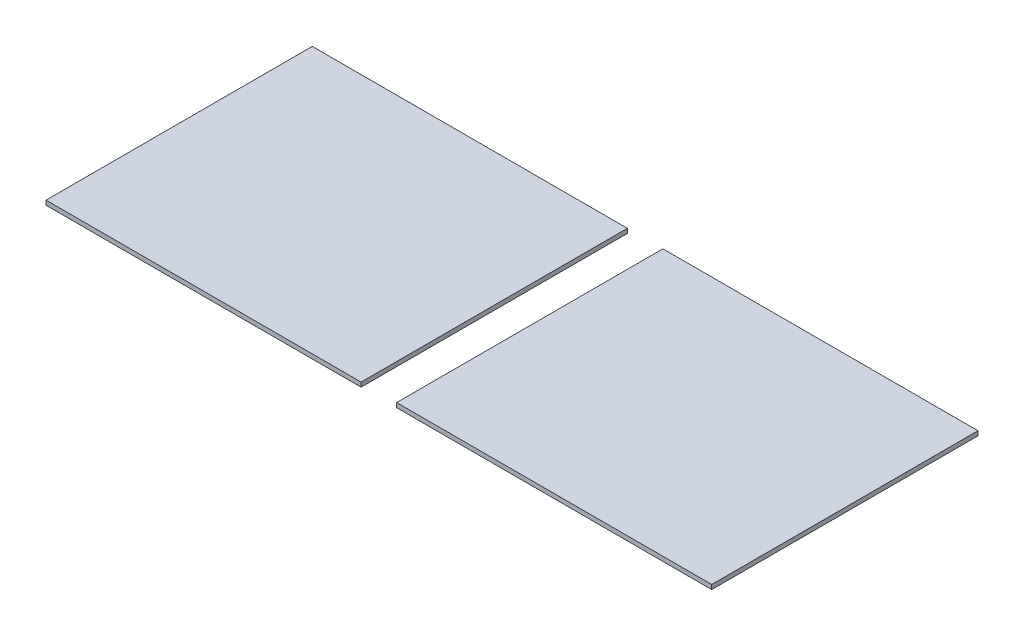
SolidWorks part; units mm, degrees
ref_plane "Front Plane" through (0, 0, 0) normal (0, 0, 1) x (1, 0, 0)
ref_plane "Top Plane" through (0, 0, 0) normal (0, 1, 0) x (1, 0, 0)
ref_plane "Right Plane" through (0, 0, 0) normal (1, 0, 0) x (0, 0, -1)
sketch "Sketch1" plane through (0, 0, 0) normal (0, 1, 0) x (1, 0, 0)
  line L1 (0, 0) -> (1219.2, 0)
  line L2 (0, 0) -> (0, 609.6)
  line L3 (0, 609.6) -> (1219.2, 609.6)
  line L4 (1219.2, 0) -> (1219.2, 609.6)
  dimension "D1" = 1219.2
  dimension "D2" = 609.6
extrude "Boss-Extrude1" add sketch "Sketch1" along normal blind 6.35
sketch "Sketch2" plane through (0, 6.35, 0) normal (0, 1, 0) x (1, 0, 0)
  line L0 (0, 0) -> (1219.2, 0) construction
  line L1 (0, 0) -> (450.85, 0)
  line L2 (0, 0) -> (0, 381)
  line L3 (0, 381) -> (450.85, 381)
  line L4 (450.85, 0) -> (450.85, 381)
  line L5 (501.65, 0) -> (952.5, 0)
  line L6 (501.65, 0) -> (501.65, 381)
  line L7 (501.65, 381) -> (952.5, 381)
  line L8 (952.5, 0) -> (952.5, 381)
  line L9 (0, 609.6) -> (1219.2, 609.6)
  line L10 (1219.2, 609.6) -> (1219.2, 0)
  line L11 (1219.2, 0) -> (952.5, 0)
  line L12 (952.5, 0) -> (952.5, 381)
  line L13 (952.5, 381) -> (501.65, 381)
  line L14 (501.65, 381) -> (501.65, 0)
  line L16 (450.85, 0) -> (450.85, 381)
  line L17 (450.85, 381) -> (0, 381)
  line L18 (0, 609.6) -> (0, 381)
  line L19 (0, 381) -> (450.85, 381)
  line L20 (450.85, 381) -> (450.85, 0)
  line L21 (450.85, 0) -> (501.65, 0)
  line L22 (501.65, 0) -> (501.65, 381)
  line L23 (501.65, 381) -> (952.5, 381)
  line L24 (952.5, 381) -> (952.5, 0)
  line L25 (952.5, 0) -> (1219.2, 0)
  line L26 (1219.2, 0) -> (1219.2, 609.6)
  line L27 (1219.2, 609.6) -> (0, 609.6)
  line L28 (450.85, 381) -> (501.65, 381)
  line L29 (450.85, 381) -> (450.85, 0)
  line L30 (450.85, 0) -> (501.65, 0)
  line L31 (501.65, 381) -> (501.65, 0)
  line L32 (0, 609.6) -> (1219.2, 609.6)
  line L33 (0, 609.6) -> (0, 381)
  line L34 (0, 381) -> (1219.2, 381)
  line L35 (1219.2, 609.6) -> (1219.2, 381)
  line L36 (952.5, 381) -> (1219.2, 381)
  line L37 (952.5, 381) -> (952.5, 0)
  line L38 (952.5, 0) -> (1219.2, 0)
  line L39 (1219.2, 381) -> (1219.2, 0)
  point P18 (0, 0)
  point P19 (0, 0)
  point P20 (0, 0)
  point P21 (501.65, 381)
  point P22 (0, 0)
  dimension "D1" = 450.85
  dimension "D2" = 381
  dimension "D3" = 450.85
  dimension "D5" = 50.8
sketch "Sketch7" plane through (0, 6.35, 0) normal (0, 1, 0) x (1, 0, 0)
  line L0 (501.65, 381) -> (952.5, 381)
  line L1 (0, 609.6) -> (1219.2, 609.6)
  line L2 (0, 609.6) -> (0, 381)
  line L3 (0, 381) -> (450.85, 381)
  line L4 (1219.2, 609.6) -> (1219.2, 381)
  line L6 (952.5, 381) -> (952.5, 0)
  line L7 (952.5, 0) -> (1219.2, 0)
  line L8 (1219.2, 381) -> (1219.2, 0)
  line L10 (450.85, 381) -> (450.85, 0)
  line L11 (450.85, 0) -> (501.65, 0)
  line L12 (501.65, 381) -> (501.65, 0)
extrude "Cut-Extrude1" cut sketch "Sketch7" against normal up to next
